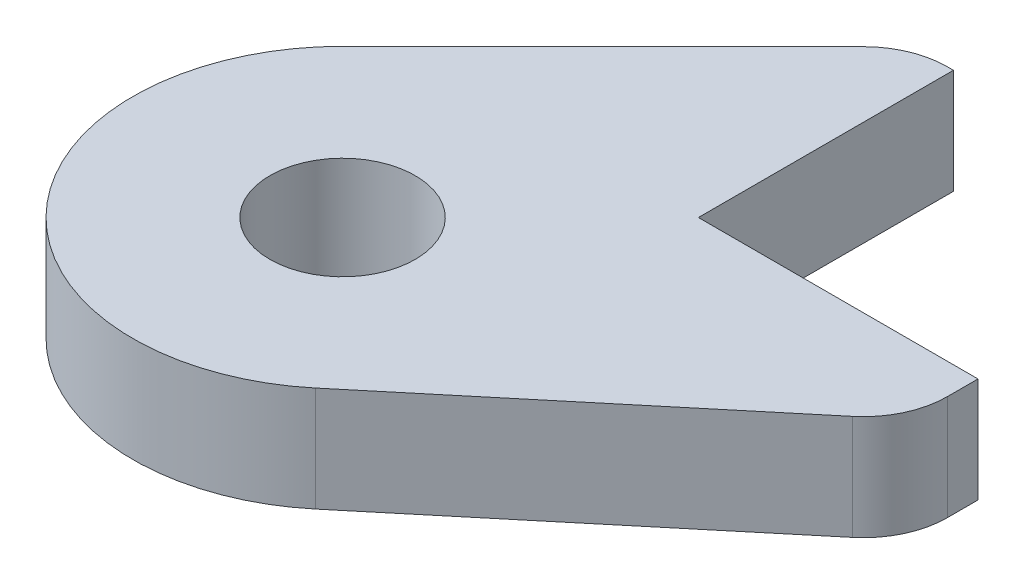
SolidWorks part; units mm, degrees
material "Alloy Steel"
ref_plane "X-Y Datum" through (0, 0, 0) normal (0, 0, 1) x (1, 0, 0)
ref_plane "X-Z Datum" through (0, 0, 0) normal (0, 1, 0) x (1, 0, 0)
ref_plane "Y-Z Datum" through (0, 0, 0) normal (1, 0, 0) x (0, 0, -1)
sketch "Sketch4" plane through (0, 0, 0) normal (0, 1, 0) x (1, 0, 0)
  line L1 (-12.7, -12.7) -> (12.7, -12.7) construction
  line L2 (-12.7, -12.7) -> (-12.7, 12.7) construction
  line L3 (-12.7, 12.7) -> (12.7, 12.7) construction
  line L4 (12.7, -12.7) -> (12.7, 12.7) construction
  line L5 (-12.7, -12.7) -> (12.7, 12.7) construction
  line L6 (-12.7, 12.7) -> (12.7, -12.7) construction
  line L8 (-12.7, -1.1159) -> (-12.7, -12.7)
  line L9 (-12.7, -12.7) -> (0, -12.7)
  line L10 (-12.7, -12.7) -> (-20.7822, -20.7822) construction
  line L12 (0, -12.7) -> (0, -15.875)
  line L13 (-12.7, -1.1159) -> (-14.5545, -1.1159)
  line L14 (-14.5545, -1.1159) -> (-27.5091, -14.0388)
  line L15 (0, -15.875) -> (-14.6882, -28.1026)
  circle A0 centre (-20.7822, -20.7822) radius 9.525 construction
  arc A3 (-27.5091, -14.0388) -> (-14.6882, -28.1026) centre (-20.7822, -20.7822) ccw
  point P0 (0, 0)
  dimension "D2" = 19.05
  dimension "D1" = 25.4
  dimension "D3" = 11.43
extrude "Boss-Extrude2" add sketch "Sketch4" along normal blind 4.7625
fillet "Fillet3" radius 3.81 2 edges at (0, 2.3813, 15.875) (-14.5545, 2.3813, 1.1159)
hole_wizard "M6 Clearance Hole3" positions "Sketch7" profile "Sketch8" hole size "M6" standard "ANSI Metric" end condition through all
sketch "Sketch7" plane through (0, 4.7625, 0) normal (0, 1, 0) x (1, 0, 0)
  point P0 (-20.7822, -20.7822)
sketch "Sketch8" plane through (-20.7822, 4.7625, 20.7822) normal (1, 0, 0) x (0, 0, 1)
  line L0 (0, 0) -> (0, 4.7625)
  line L1 (0, 4.7625) -> (3.3, 4.7625)
  line L2 (3.3, 4.7625) -> (3.3, 0)
  line L5 (3.3, 0) -> (0, 0)
  line L11 (0, -6.35) -> (0, 107.95) construction
  dimension "Thru Hole Dia." = 6.6
  dimension "Thru Hole Depth" = 4.7625
